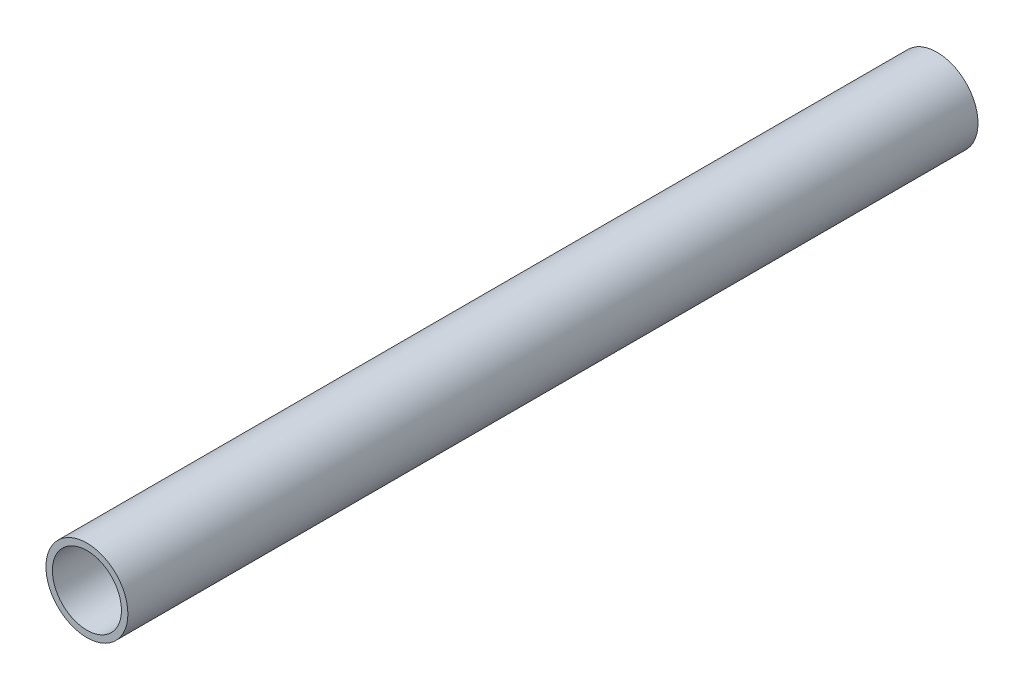
SolidWorks part; units mm, degrees
material "E-Glass Fiber"
ref_plane "Ön Düzlem" through (0, 0, 0) normal (0, 0, 1) x (1, 0, 0)
ref_plane "Üst Düzlem" through (0, 0, 0) normal (0, 1, 0) x (1, 0, 0)
ref_plane "Sağ Düzlem" through (0, 0, 0) normal (1, 0, 0) x (0, 0, -1)
sketch "Sketch1" plane through (0, 0, 0) normal (0, 0, 1) x (1, 0, 0)
  circle A0 centre (0, 0) radius 44.5
  circle A1 centre (0, 0) radius 37.5
  dimension "D1" = 7
  dimension "D2" = 89
extrude "Boss-Extrude1" add sketch "Sketch1" along normal mid plane 923
